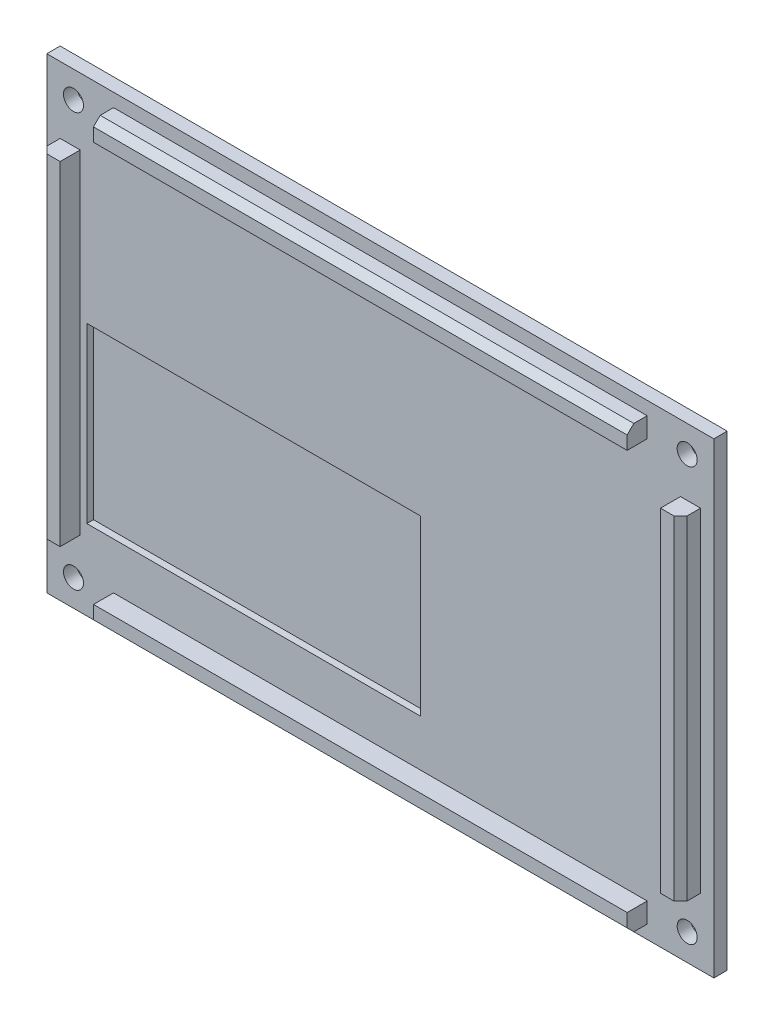
SolidWorks part; units mm, degrees
ref_plane "Ebene vorne" through (0, 0, 0) normal (0, 0, 1) x (1, 0, 0)
ref_plane "Ebene oben" through (0, 0, 0) normal (0, 1, 0) x (1, 0, 0)
ref_plane "Ebene rechts" through (0, 0, 0) normal (1, 0, 0) x (0, 0, -1)
sketch "Skizze1" plane through (0, 0, 0) normal (0, 0, 1) x (1, 0, 0)
  line L1 (0, 0) -> (100, 0)
  line L2 (0, 0) -> (0, -70)
  line L3 (0, -70) -> (100, -70)
  line L4 (100, 0) -> (100, -70)
  dimension "D1" = 100
  dimension "D2" = 70
extrude "Aufsatz-Linear austragen1" add sketch "Skizze1" along normal blind 2
sketch "Skizze2" plane through (0, 0, 2) normal (0, 0, 1) x (1, 0, 0)
  line L0 (100, 0) -> (0, 0) construction
  line L1 (10, -2) -> (90, -2)
  line L2 (10, -2) -> (10, -5)
  line L3 (10, -5) -> (90, -5)
  line L4 (90, -2) -> (90, -5)
  line L5 (10, -68) -> (90, -68)
  line L6 (10, -68) -> (10, -65)
  line L7 (10, -65) -> (90, -65)
  line L8 (90, -68) -> (90, -65)
  line L9 (98, -10) -> (95, -10)
  line L10 (98, -10) -> (98, -60)
  line L11 (98, -60) -> (95, -60)
  line L12 (95, -10) -> (95, -60)
  line L13 (2, -10) -> (5, -10)
  line L14 (2, -10) -> (2, -60)
  line L15 (2, -60) -> (5, -60)
  line L16 (5, -10) -> (5, -60)
  line L17 (100, -70) -> (100, 0) construction
  line L18 (0, 0) -> (0, -70) construction
  line L19 (0, -70) -> (100, -70) construction
  dimension "D1" = 3
  dimension "D2" = 3
  dimension "D3" = 3
  dimension "D4" = 3
  dimension "D5" = 2
  dimension "D6" = 2
  dimension "D7" = 2
  dimension "D8" = 2
  dimension "D9" = 10
  dimension "D10" = 10
  dimension "D11" = 10
  dimension "D12" = 10
  dimension "D13" = 10
  dimension "D14" = 10
  dimension "D15" = 10
  dimension "D16" = 10
extrude "Aufsatz-Linear austragen2" add sketch "Skizze2" along normal blind 3
chamfer "Fase1" distance 1 angle 45 4 edges at (50, -68, 5) (98, -35, 5) (2, -35, 5) (50, -2, 5)
sketch "Skizze3" plane through (0, 0, 2) normal (0, 0, 1) x (1, 0, 0)
  line L0 (100, 0) -> (0, 0) construction
  line L1 (0, 0) -> (0, -70) construction
  line L2 (100, -70) -> (100, 0) construction
  line L3 (0, -70) -> (100, -70) construction
  circle A0 centre (4, -4) radius 1.5
  circle A1 centre (96, -4) radius 1.5
  circle A2 centre (96, -66) radius 1.5
  circle A3 centre (4, -66) radius 1.5
  dimension "D1" = 3
  dimension "D2" = 3
  dimension "D3" = 3
  dimension "D4" = 3
  dimension "D5" = 4
  dimension "D6" = 4
  dimension "D7" = 4
  dimension "D8" = 4
  dimension "D9" = 4
  dimension "D10" = 4
  dimension "D11" = 4
  dimension "D12" = 4
extrude "Schnitt-Linear austragen1" cut sketch "Skizze3" against normal through all contours A1 | A2 | A3 | A0
sketch "Skizze4" plane through (0, 0, 0) normal (0, 0, -1) x (-1, 0, 0)
  line L0 (0, -70) -> (-100, -70) construction
  line L1 (-56, -32) -> (-6, -32)
  line L2 (-56, -32) -> (-56, -58)
  line L3 (-56, -58) -> (-6, -58)
  line L4 (-6, -32) -> (-6, -58)
  line L5 (0, 0) -> (0, -70) construction
  dimension "D1" = 26
  dimension "D2" = 50
  dimension "D3" = 12
  dimension "D4" = 6
extrude "Schnitt-Linear austragen2" cut sketch "Skizze4" against normal blind 0.01
sketch "Skizze6" plane through (0, 0, 2) normal (0, 0, 1) x (1, 0, 0)
  line L0 (56, -32) -> (56, -58) construction
  line L1 (56, -58) -> (6, -58) construction
  line L2 (6, -58) -> (6, -32) construction
  line L3 (6, -32) -> (56, -32) construction
  line L4 (56, -32) -> (56, -58)
  line L5 (56, -58) -> (6, -58)
  line L6 (6, -58) -> (6, -32)
  line L7 (6, -32) -> (56, -32)
extrude "Schnitt-Linear austragen3" cut sketch "Skizze6" against normal blind 1
